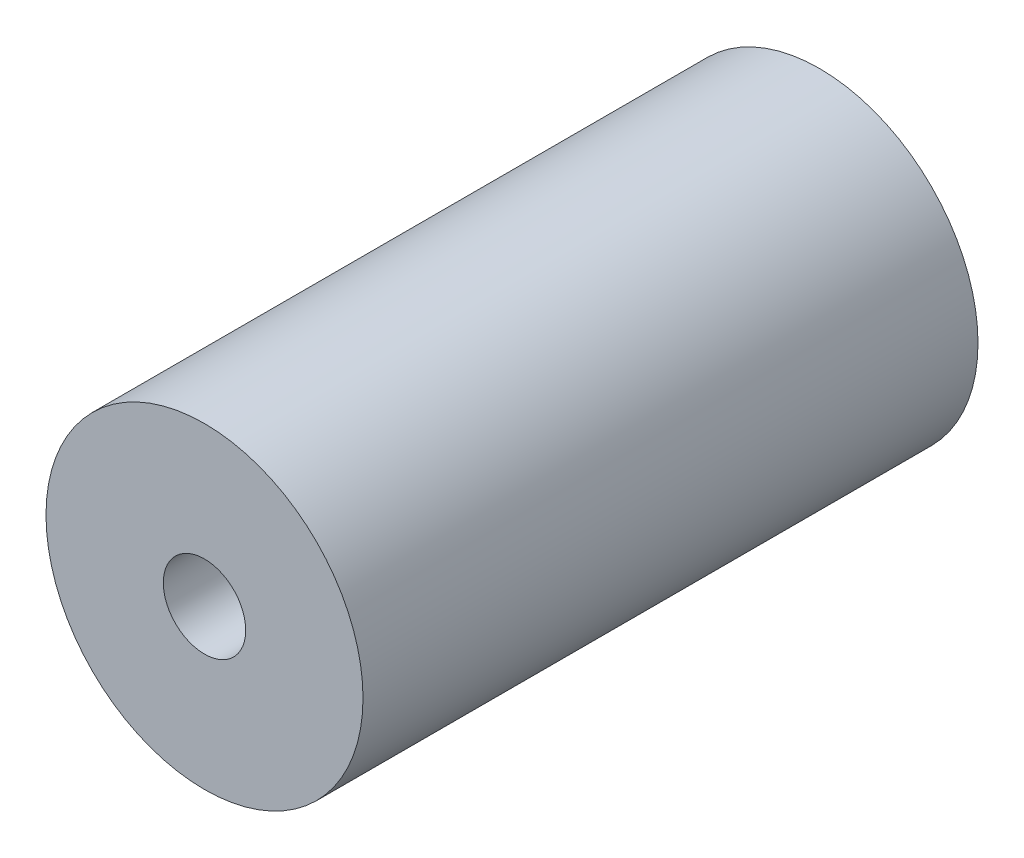
SolidWorks part; units mm, degrees
material "1060 合金"
ref_plane "正面" through (0, 0, 0) normal (0, 0, 1) x (1, 0, 0)
ref_plane "平面" through (0, 0, 0) normal (0, 1, 0) x (1, 0, 0)
ref_plane "右側面" through (0, 0, 0) normal (1, 0, 0) x (0, 0, -1)
sketch "ｽｹｯﾁ1" plane through (0, 0, 0) normal (0, 0, 1) x (1, 0, 0)
  circle A0 centre (0, 0) radius 5
  circle A1 centre (0, 0) radius 1.3
  dimension "D1" = 2.6
  dimension "D2" = 10
extrude "ﾎﾞｽ - 押し出し1" add sketch "ｽｹｯﾁ1" along normal blind 19.4
